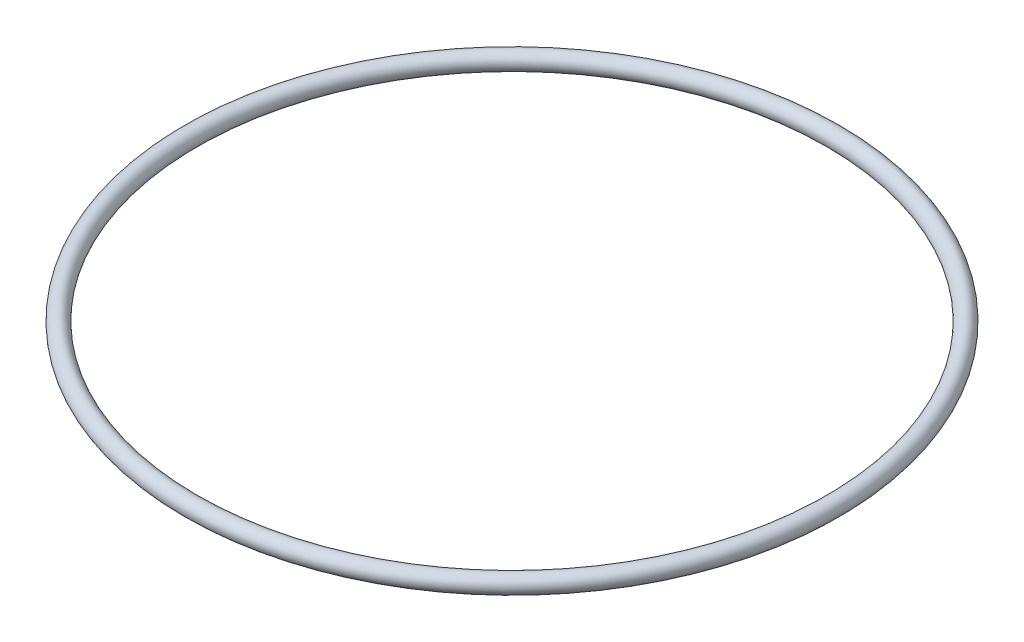
SolidWorks part; units mm, degrees
ref_plane "Спереди" through (0, 0, 0) normal (0, 0, 1) x (1, 0, 0)
ref_plane "Сверху" through (0, 0, 0) normal (0, 1, 0) x (1, 0, 0)
ref_plane "Справа" through (0, 0, 0) normal (1, 0, 0) x (0, 0, -1)
sketch "Эскиз1" plane through (0, 0, 0) normal (0, 0, 1) x (1, 0, 0)
  line L0 (0, 8.1364) -> (0, -6.5679) construction
  circle A0 centre (54.7059, 0) radius 1.5
  dimension "D1" = 3
  dimension "D2" = 54.7059
revolve "Повернуть1" add sketch "Эскиз1" angle 360 about L0
